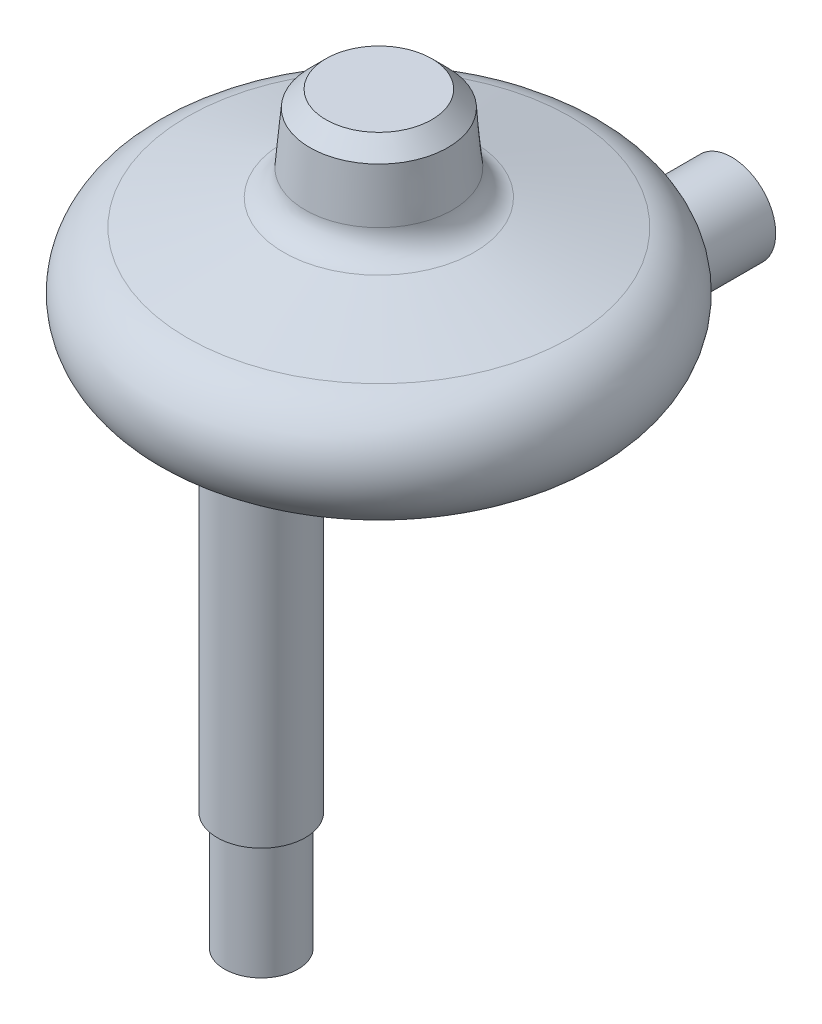
SolidWorks part; units mm, degrees
ref_plane "Front" through (0, 0, 0) normal (0, 0, 1) x (1, 0, 0)
ref_plane "Top" through (0, 0, 0) normal (0, 1, 0) x (1, 0, 0)
ref_plane "Right" through (0, 0, 0) normal (1, 0, 0) x (0, 0, -1)
sketch "Sketch1" plane through (0, 0, 0) normal (0, 0, 1) x (1, 0, 0)
  line L0 (0, 0) -> (0, 69.3536) construction
  line L1 (0, 0) -> (19.05, 0)
  line L2 (20.6935, 12.4836) -> (0, 18.0284)
  line L4 (0, 18.0284) -> (0, 0)
  arc A0 (19.05, 0) -> (20.6935, 12.4836) centre (19.05, 6.35) ccw
  dimension "D2" = 6.35
  dimension "D1" = 50.8
  dimension "D3" = 15
revolve "Base-Revolve" add sketch "Sketch1" angle 360 about L0
sketch "Sketch2" plane through (0, 0, 0) normal (0, -1, 0) x (1, 0, 0)
  circle A0 centre (0, 0) radius 9.525
  dimension "D1" = 19.05
extrude "Boss-Extrude1" add sketch "Sketch2" against normal blind 25.4 draft 5
fillet "Fillet1" radius 3.175 1 edges at (0, 15.8477, 8.1385)
sketch "Sketch3" plane through (0, 0, 0) normal (0, -1, 0) x (1, 0, 0)
  circle A0 centre (0, 12.7) radius 4.7625
  dimension "D1" = 9.525
  dimension "D2" = 12.7
extrude "Boss-Extrude2" add sketch "Sketch3" along normal blind 35.875
fillet "Fillet2" radius 3.175 1 edges at (0, 0, 7.9375)
ref_plane "Plane4" through (0, 0, -6.35) normal (0, 0, 1) x (1, 0, 0)
sketch "Sketch4" plane through (0, 0, -6.35) normal (0, 0, 1) x (1, 0, 0)
  line L1 (-4.7625, 1.5875) -> (4.7625, 1.5875)
  line L2 (-4.7625, 1.5875) -> (-4.7625, -4.7625)
  line L3 (4.7625, -4.7625) -> (4.7625, 1.5875)
  line L4 (-19.05, 0) -> (19.05, 0) construction
  arc A0 (-4.7625, -4.7625) -> (4.7625, -4.7625) centre (0, -4.7625) ccw
  dimension "D1" = 4.7625
  dimension "D2" = 6.35
  dimension "D3" = 1.5875
extrude "Boss-Extrude3" add sketch "Sketch4" against normal blind 19.05
fillet "Fillet4" radius 1.5875 3 edges at (4.7625, -2.3812, -6.35) (-4.7625, -2.3812, -6.35) (0, -9.525, -6.35)
fillet "Fillet8" radius 1.5875 7 edges at (4.7625, 12.0396, -15.5158) (-4.7625, 12.5632, -17.0875) (4.7625, 0, -13.1913) (0, 0, -6.35) (-4.7625, 0, -13.1913) (4.2975, 0, -6.815) (-4.2975, 0, -6.815)
chamfer "Chamfer1" distance 1.5875 angle 45 1 edges at (0, 25.4, -7.3028)
sketch "Sketch5" plane through (0, 0, -25.4) normal (0, 0, -1) x (-1, 0, 0)
  circle A0 centre (0, -4.7625) radius 4.7625
  arc A1 (-4.7625, -4.7625) -> (4.7625, -4.7625) centre (0, -4.7625) ccw construction
extrude "Boss-Extrude4" add sketch "Sketch5" along normal blind 12.7
sketch "Sketch6" plane through (0, -35.875, 0) normal (0, -1, 0) x (1, 0, 0)
  circle A1 centre (0, 12.7) radius 3.9687
  circle A2 centre (0, 12.7) radius 3.9687
  dimension "D1" = 0.7937
extrude "Boss-Extrude5" add sketch "Sketch6" along normal blind 12.7
